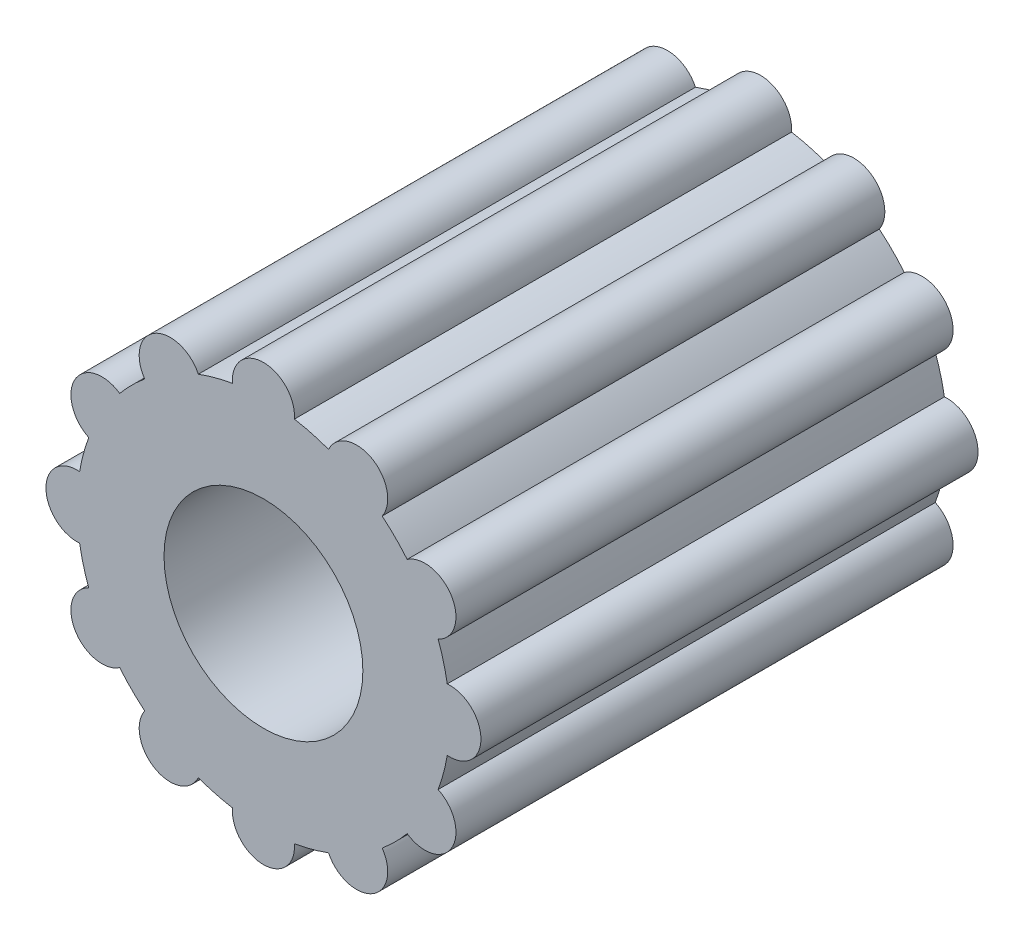
SolidWorks part; units mm, degrees
ref_plane "Plan de face" through (0, 0, 0) normal (0, 0, 1) x (1, 0, 0)
ref_plane "Plan de dessus" through (0, 0, 0) normal (0, 1, 0) x (1, 0, 0)
ref_plane "Plan de droite" through (0, 0, 0) normal (1, 0, 0) x (0, 0, -1)
sketch "Esquisse1" plane through (0, 0, 0) normal (0, 0, 1) x (1, 0, 0)
  arc A0 (0.2491, 1.4792) -> (-0.2491, 1.4792) centre (0, 1.5) ccw
  arc A1 (-0.5238, 1.4056) -> (-0.9553, 1.1564) centre (-0.75, 1.299) ccw
  arc A2 (-1.1564, 0.9553) -> (-1.4056, 0.5238) centre (-1.299, 0.75) ccw
  arc A3 (-1.4792, 0.2491) -> (-1.4792, -0.2491) centre (-1.5, 0) ccw
  arc A4 (-1.4056, -0.5238) -> (-1.1564, -0.9553) centre (-1.299, -0.75) ccw
  arc A5 (-0.9553, -1.1564) -> (-0.5238, -1.4056) centre (-0.75, -1.299) ccw
  arc A6 (-0.2491, -1.4792) -> (0.2491, -1.4792) centre (0, -1.5) ccw
  arc A7 (0.5238, -1.4056) -> (0.9553, -1.1564) centre (0.75, -1.299) ccw
  arc A8 (1.1564, -0.9553) -> (1.4056, -0.5238) centre (1.299, -0.75) ccw
  arc A9 (1.4792, -0.2491) -> (1.4792, 0.2491) centre (1.5, 0) ccw
  arc A10 (1.4056, 0.5238) -> (1.1564, 0.9553) centre (1.299, 0.75) ccw
  arc A11 (0.9553, 1.1564) -> (0.5238, 1.4056) centre (0.75, 1.299) ccw
  arc A12 (0.5238, 1.4056) -> (0.2491, 1.4792) centre (0, 0) ccw
  arc A13 (-0.2491, 1.4792) -> (-0.5238, 1.4056) centre (0, 0) ccw
  arc A14 (-0.9553, 1.1564) -> (-1.1564, 0.9553) centre (0, 0) ccw
  arc A15 (-1.4056, 0.5238) -> (-1.4792, 0.2491) centre (0, 0) ccw
  arc A16 (-1.4792, -0.2491) -> (-1.4056, -0.5238) centre (0, 0) ccw
  arc A17 (-1.1564, -0.9553) -> (-0.9553, -1.1564) centre (0, 0) ccw
  arc A18 (-0.5238, -1.4056) -> (-0.2491, -1.4792) centre (0, 0) ccw
  arc A19 (0.2491, -1.4792) -> (0.5238, -1.4056) centre (0, 0) ccw
  arc A20 (0.9553, -1.1564) -> (1.1564, -0.9553) centre (0, 0) ccw
  arc A21 (1.4056, -0.5238) -> (1.4792, -0.2491) centre (0, 0) ccw
  arc A22 (1.4792, 0.2491) -> (1.4056, 0.5238) centre (0, 0) ccw
  arc A23 (1.1564, 0.9553) -> (0.9553, 1.1564) centre (0, 0) ccw
extrude "Boss.-Extru.1" add sketch "Esquisse1" along normal blind 4
hole_wizard "Trou taraudé M21" positions "Esquisse3D2" profile "Esquisse3" tap size "M2" standard "ISO" end condition through all
sketch3d "Esquisse3D2"
  point P0 (0, 0, 0)
  point P3 (0, 0, 0)
cosmetic thread "Filetage de perçage1" parameters "D2"=2
cosmetic thread "Filetage de perçage2" parameters "D2"=2
sketch "Esquisse3" plane through (0, 0, 0) normal (1, 0, 0) x (0, 1, 0)
  line L0 (0, 0) -> (0, 4)
  line L1 (0, 4) -> (0.8, 4)
  line L2 (0.8, 4) -> (0.8, 0)
  line L5 (0.8, 0) -> (0, 0)
  line L11 (0, -6.35) -> (0, 107.95) construction
  dimension "Diamètre du trou pour taraudage jusqu'au prochain" = 1.6
  dimension "Profondeur du trou pour taraudage jusqu'au prochain" = 4
